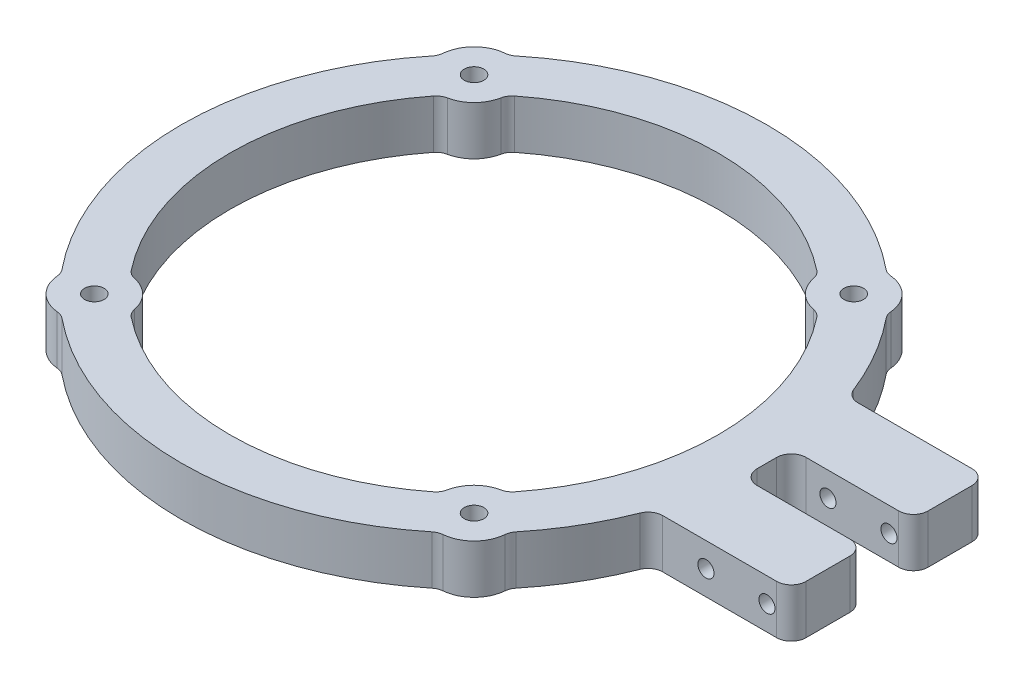
SolidWorks part; units mm, degrees
material "6063-T83"
ref_plane "Front Plane" through (0, 0, 0) normal (0, 0, 1) x (1, 0, 0)
ref_plane "Top Plane" through (0, 0, 0) normal (0, 1, 0) x (1, 0, 0)
ref_plane "Right Plane" through (0, 0, 0) normal (1, 0, 0) x (0, 0, -1)
sketch "Sketch1" plane through (0, 0, 0) normal (0, 1, 0) x (1, 0, 0)
  line L0 (0, -50) -> (0, -60) construction
  line L1 (0, 0) -> (0, -50) construction
  line L2 (56.5685, -20) -> (85, -20)
  line L3 (85, -20) -> (85, -5)
  line L4 (85, -5) -> (60, -5)
  line L5 (60, -5) -> (60, 5)
  line L6 (60, 5) -> (85, 5)
  line L7 (85, 5) -> (85, 20)
  line L8 (85, 20) -> (56.5685, 20)
  circle A0 centre (0, 0) radius 50
  circle A1 centre (0, 0) radius 60 construction
  arc A2 (56.5685, 20) -> (56.5685, -20) centre (0, 0) ccw
  dimension "D1" = 100
  dimension "D2" = 10
  dimension "D3" = 10
  dimension "D4" = 15
  dimension "D6" = 25
extrude "Boss-Extrude1" add sketch "Sketch1" along normal blind 10
sketch "Sketch3" plane through (0, 10, 0) normal (0, 1, 0) x (1, 0, 0)
  line L0 (38.8909, 38.8909) -> (38.8909, -38.8909) construction
  line L1 (60, -5) -> (60, 5) construction
  circle A0 centre (0, 0) radius 55 construction
  circle A1 centre (38.8909, -38.8909) radius 7
  circle A2 centre (-38.8909, -38.8909) radius 7
  circle A3 centre (-38.8909, 38.8909) radius 7
  circle A4 centre (38.8909, 38.8909) radius 7
  point P14 (0, 0)
  dimension "D1" = 110
  dimension "D2" = 14
  dimension "D3" = 4
extrude "Boss-Extrude2" add sketch "Sketch3" against normal up to surface (10 mm away) up to face at (57.0711, 0, 0)
sketch "Sketch4" plane through (0, 10, 0) normal (0, 1, 0) x (1, 0, 0)
  circle A0 centre (38.8909, -38.8909) radius 2
  circle A1 centre (-38.8909, -38.8909) radius 2
  circle A2 centre (-38.8909, 38.8909) radius 2
  circle A3 centre (38.8909, 38.8909) radius 2
  point P12 (0, 0)
  dimension "D1" = 4
  dimension "D2" = 4
extrude "Cut-Extrude1" cut sketch "Sketch4" against normal blind 10
hole_wizard "M4x0.7 Tapped Hole1" positions "Sketch7" profile "Sketch8" tap size "M4x0.7" standard "ANSI Metric"
sketch "Sketch7" plane through (0, 0, 5) normal (0, 0, -1) x (-1, 0, 0)
  line L0 (-85, 5) -> (-60, 5) construction
  line L1 (-85, 10) -> (-85, 0) construction
  line L2 (-60, 10) -> (-60, 0) construction
  point P0 (-80, 5)
  point P2 (-67.5, 5)
  dimension "D1" = 5
  dimension "D2" = 7.5
sketch "Sketch8" plane through (80, 5, 5) normal (1, 0, 0) x (0, 1, 0)
  line L0 (0, 0) -> (0, 55)
  line L1 (0, 55) -> (1.65, 55)
  line L2 (1.65, 55) -> (1.65, 0)
  line L5 (1.65, 0) -> (0, 0)
  line L11 (0, -6.35) -> (0, 107.95) construction
  dimension "Thru Tap Drill Dia." = 3.3
  dimension "Thru Tap Drill Depth" = 55
cosmetic thread "Hole Thread1" parameters "D2"=4
cosmetic thread "Hole Thread2" parameters "D2"=4
hole_wizard "M4x0.7 Tapped Hole2" positions "Sketch9" profile "Sketch10" tap size "M4x0.7" standard "ANSI Metric" end condition through all
sketch "Sketch9" plane through (0, 0, -5) normal (0, 0, 1) x (1, 0, 0)
  line L0 (85, 5) -> (60, 5) construction
  line L1 (85, 10) -> (85, 0) construction
  line L2 (60, 10) -> (60, 0) construction
  point P0 (80, 5)
  point P2 (67.5, 5)
  dimension "D1" = 7.5
  dimension "D2" = 5
sketch "Sketch10" plane through (80, 5, -5) normal (1, 0, 0) x (0, -1, 0)
  line L0 (0, 0) -> (0, 55)
  line L1 (0, 55) -> (1.65, 55)
  line L2 (1.65, 55) -> (1.65, 0)
  line L5 (1.65, 0) -> (0, 0)
  line L11 (0, -6.35) -> (0, 107.95) construction
  dimension "Thru Tap Drill Dia." = 3.3
  dimension "Thru Tap Drill Depth" = 55
cosmetic thread "Hole Thread3" parameters "D2"=4
cosmetic thread "Hole Thread4" parameters "D2"=4
fillet "Fillet1" radius 3 24 edges at (85, 5, -20) (85, 5, -5) (85, 5, 5) (85, 5, 20) (31.9018, 5, 38.5003) (38.5003, 5, 31.9018) (38.5003, 5, -31.9018) (31.9018, 5, -38.5003) (-31.9018, 5, -38.5003) (-38.5003, 5, -31.9018) (-38.6573, 5, -45.887) (-45.887, 5, -38.6573) (45.887, 5, -38.6573) (38.6573, 5, -45.887) (-38.5003, 5, 31.9018) (-31.9018, 5, 38.5003) (-45.887, 5, 38.6573) (-38.6573, 5, 45.887) (38.6573, 5, 45.887) (45.887, 5, 38.6573) (56.5685, 5, 20) (56.5685, 5, -20) (60, 5, 5) (60, 5, -5)
